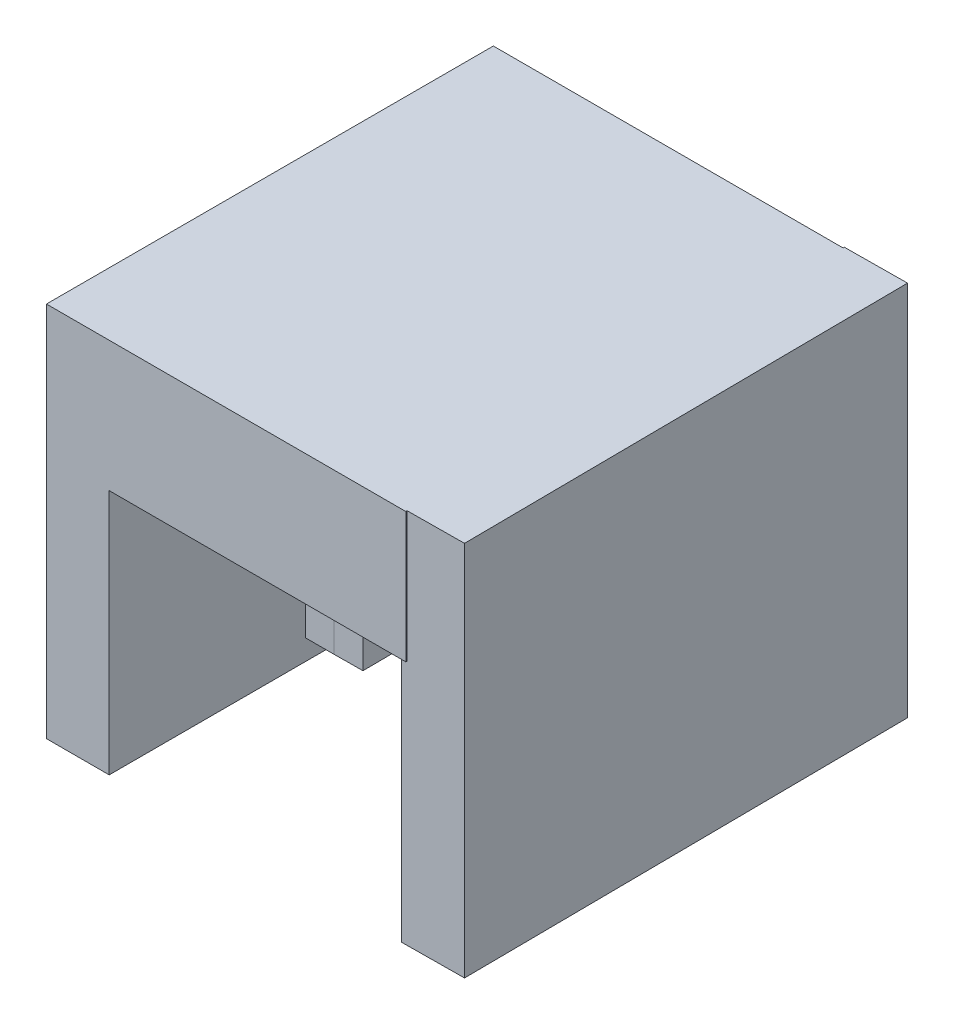
SolidWorks part; units mm, degrees
ref_plane "Front Plane" through (0, 0, 0) normal (0, 0, 1) x (1, 0, 0)
ref_plane "Top Plane" through (0, 0, 0) normal (0, 1, 0) x (1, 0, 0)
ref_plane "Right Plane" through (0, 0, 0) normal (1, 0, 0) x (0, 0, -1)
sketch "Sketch1" plane through (0, 0, 0) normal (0, 1, 0) x (1, 0, 0)
  line L0 (118.5, 375) -> (592.5, 375) construction
  line L1 (27.997, 26.1044) -> (30.497, 26.1044)
  line L2 (32.9969, 26.126) -> (30.497, 26.1044)
  line L3 (32.9969, 26.126) -> (32.9463, 31.9923)
  line L4 (43.0882, 40.7909) -> (40.3953, 39.9592)
  line L5 (42.9365, 58.3777) -> (43.0882, 40.7909)
  line L6 (48.4363, 58.4251) -> (42.9365, 58.3777)
  line L7 (48.7742, 19.251) -> (48.4363, 58.4251)
  line L8 (43.2744, 19.2036) -> (48.7742, 19.251)
  line L9 (43.1362, 35.2238) -> (43.2744, 19.2036)
  line L10 (40.4315, 35.7538) -> (43.1362, 35.2238)
  line L11 (24.9791, 40.7283) -> (20.4796, 39.8733)
  line L12 (25.0572, 34.5446) -> (20.4796, 35.6677)
  line L13 (20.4796, 35.6677) -> (17.7796, 35.1144)
  line L14 (17.7796, 35.1144) -> (17.7796, 19.0937)
  line L15 (17.7796, 19.0937) -> (12.2796, 19.0937)
  line L16 (12.2796, 19.0937) -> (12.2796, 58.2692)
  line L17 (12.2796, 58.2692) -> (17.7796, 58.2692)
  line L18 (17.7796, 58.2692) -> (17.7796, 40.6817)
  line L19 (17.7796, 40.6817) -> (20.4796, 39.8733)
  line L20 (35.8639, 34.5912) -> (40.4315, 35.7538)
  line L21 (27.997, 26.1044) -> (27.997, 31.971)
  line L22 (35.8886, 40.7754) -> (40.3953, 39.9592)
  arc A0 (25.0572, 34.5446) -> (27.997, 31.971) centre (30.4202, 37.7047) ccw
  arc A1 (30.4202, 43.9295) -> (24.9791, 40.7283) centre (30.4202, 37.7047) ccw
  arc A2 (30.4202, 43.9295) -> (35.8886, 40.7754) centre (30.4738, 37.7049) cw
  arc A3 (35.8639, 34.5912) -> (32.9463, 31.9923) centre (30.4738, 37.7049) cw
  dimension "D9" = 30.4202
  dimension "D2" = 6.2248
  dimension "D1" = 39.1755
  dimension "D3" = 12.2796
  dimension "D4" = 5.5
  dimension "D5" = 7.2775
  dimension "D6" = 19.0937
  dimension "D7" = 27.997
  dimension "D8" = 7.1994
  dimension "D10" = 30.497
  dimension "D11" = 4.2056
  dimension "D12" = 17.5875
  dimension "D13" = 16.0208
  dimension "D14" = 26.1044
  dimension "D15" = 31.971
  dimension "D16" = 30.4738
  dimension "D17" = 35.8639
  dimension "D18" = 2.7
  dimension "D19" = 2.7
  dimension "D20" = 35.8886
  dimension "D21" = 40.3953
  dimension "D22" = 40.4315
extrude "Boss-Extrude1" add sketch "Sketch1" along normal blind 33
sketch "Sketch2" plane through (0, 0, 0) normal (0, -1, 0) x (1, 0, 0)
  line L0 (17.7796, -35.1144) -> (17.7796, -40.6817)
  line L1 (17.7796, -40.6817) -> (20.4796, -39.8733)
  line L2 (20.4796, -39.8733) -> (24.9791, -40.7283)
  line L4 (25.0572, -34.5446) -> (20.4796, -35.6677)
  line L5 (27.997, -31.971) -> (27.997, -26.1044)
  line L6 (27.997, -26.1044) -> (32.9969, -26.126)
  line L7 (32.9969, -26.126) -> (32.9463, -31.9923)
  line L8 (35.8639, -34.5912) -> (40.4315, -35.7538)
  line L9 (40.4315, -35.7538) -> (43.1362, -35.2238)
  line L10 (43.1362, -35.2238) -> (43.0882, -40.7909)
  line L11 (43.0882, -40.7909) -> (40.3953, -39.9592)
  line L12 (40.3953, -39.9592) -> (35.8886, -40.7754)
  arc A0 (25.0572, -34.5446) -> (27.997, -31.971) centre (30.4202, -37.7047) cw
  arc A1 (32.9463, -31.9923) -> (35.8639, -34.5912) centre (30.4738, -37.7049) cw
  arc A2 (24.9791, -40.7283) -> (30.4202, -43.9295) centre (30.4202, -37.7047) ccw
  arc A3 (30.4202, -43.9295) -> (35.8886, -40.7754) centre (30.4202, -37.6119) ccw
extrude "Cut-Extrude1" cut sketch "Sketch2" against normal blind 12 and the other way through all
sketch "Sketch3" plane through (0, 0, -26.1044) normal (0, 0, 1) x (1, 0, 0)
  line L0 (30.497, 33) -> (30.497, 0) construction
  line L1 (27.997, 12) -> (37.4782, 12)
  line L2 (27.997, 12) -> (27.997, -5.0217)
  line L3 (27.997, -5.0217) -> (37.4782, -5.0217)
  line L4 (37.4782, 12) -> (37.4782, -5.0217)
  line L5 (27.997, 33) -> (30.497, 33) construction
  dimension "D1" = 6.9812
  dimension "D2" = 38.0217
extrude "Cut-Extrude2" cut sketch "Sketch3" against normal blind 22
sketch "Sketch6" plane through (17.7796, 0, 0) normal (1, 0, 0) x (0, 0, -1)
  line L0 (58.2692, 33) -> (58.2692, 0) construction
  line L1 (19.0937, 33) -> (58.2692, 33)
  line L2 (19.0937, 33) -> (19.0937, 21.584)
  line L3 (19.0937, 21.584) -> (58.2692, 21.584)
  line L4 (58.2692, 33) -> (58.2692, 21.584)
  line L5 (19.0937, 0) -> (58.2692, 0) construction
  dimension "D1" = 17.5875
  dimension "D2" = 21.584
extrude "Boss-Extrude3" add sketch "Sketch6" along normal blind 26
